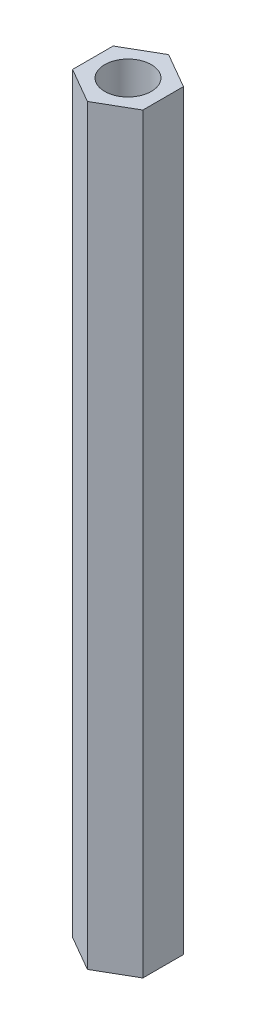
SolidWorks part; units mm, degrees
material "黄铜"
ref_plane "前视基准面" through (0, 0, 0) normal (0, 0, 1) x (1, 0, 0)
ref_plane "上视基准面" through (0, 0, 0) normal (0, 1, 0) x (1, 0, 0)
ref_plane "右视基准面" through (0, 0, 0) normal (1, 0, 0) x (0, 0, -1)
sketch "草图1" plane through (0, 0, 0) normal (0, 1, 0) x (1, 0, 0)
  line L1 (0, 2.7) -> (-2.3383, 1.35)
  line L2 (-2.3383, 1.35) -> (-2.3383, -1.35)
  line L3 (-2.3383, -1.35) -> (0, -2.7)
  line L4 (0, -2.7) -> (2.3383, -1.35)
  line L5 (2.3383, -1.35) -> (2.3383, 1.35)
  line L6 (2.3383, 1.35) -> (0, 2.7)
  circle A0 centre (0, 0) radius 2.7 construction
  circle A1 centre (0, 0) radius 1.55
  dimension "D1" = 3.1
extrude "凸台-拉伸1" add sketch "草图1" along normal blind 50
